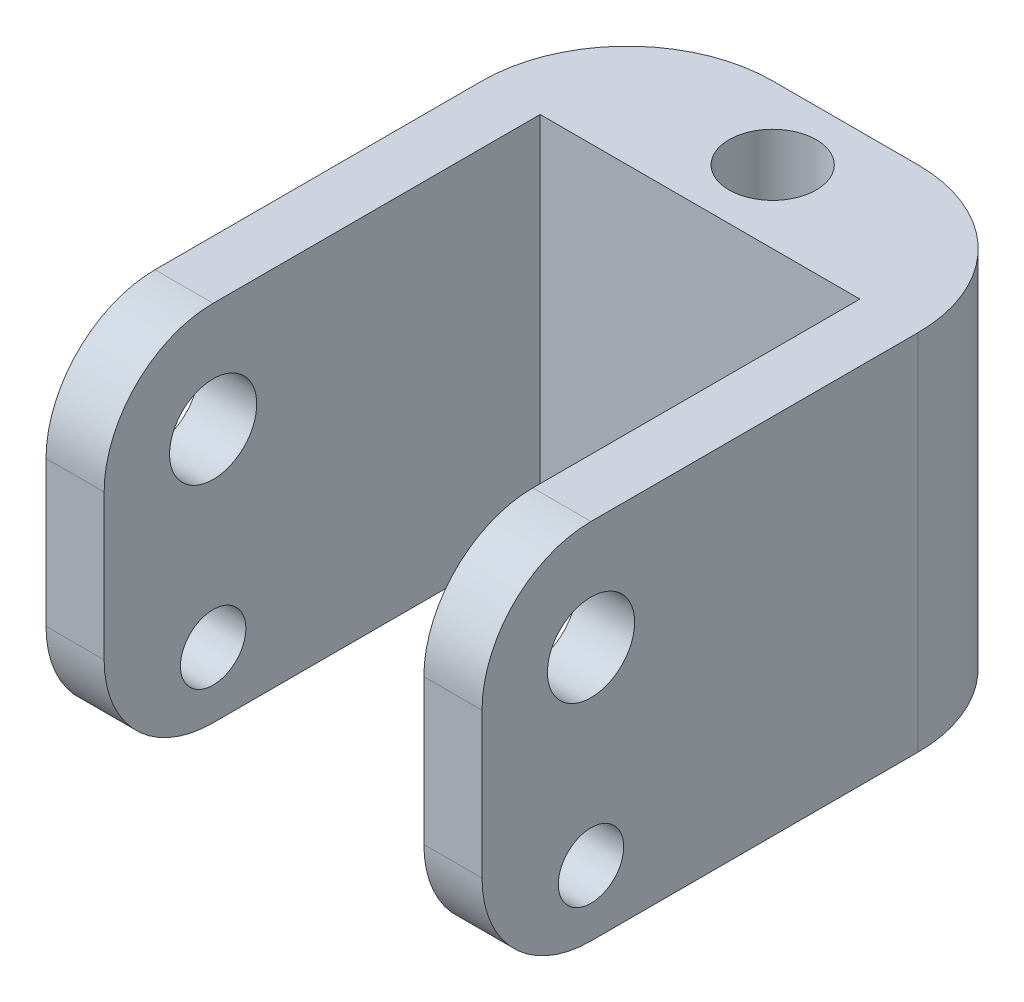
SolidWorks part; units mm, degrees
ref_plane "Front Plane" through (0, 0, 0) normal (0, 0, 1) x (1, 0, 0)
ref_plane "Top Plane" through (0, 0, 0) normal (0, 1, 0) x (1, 0, 0)
ref_plane "Right Plane" through (0, 0, 0) normal (1, 0, 0) x (0, 0, -1)
sketch "Sketch4" plane through (0, 0, 0) normal (1, 0, 0) x (0, 0, -1)
  line L1 (-40, -25) -> (40, -25)
  line L2 (-40, -25) -> (-40, 25)
  line L3 (-40, 25) -> (40, 25)
  line L4 (40, -25) -> (40, 25)
  line L5 (-40, -25) -> (40, 25) construction
  line L6 (-40, 25) -> (40, -25) construction
  line L7 (-25, 10) -> (-25, -16) construction
  circle A0 centre (-25, 10) radius 6
  circle A1 centre (-25, -16) radius 4.5
  circle A2 centre (-25, 10) radius 26 construction
  point P0 (0, 0)
  dimension "D3" = 12
  dimension "D4" = 15
  dimension "D5" = 15
  dimension "D6" = 9
  dimension "D7" = 52
  dimension "D1" = 50
  dimension "D2" = 80
extrude "Boss-Extrude2" add sketch "Sketch4" along normal mid plane 60
sketch "Sketch5" plane through (0, 0, 0) normal (0, 1, 0) x (1, 0, 0)
  line L0 (30, -40) -> (-30, -40) construction
  line L1 (-22, -40) -> (22, -40)
  line L2 (-22, -40) -> (-22, 20)
  line L3 (-22, 20) -> (22, 20)
  line L4 (22, -40) -> (22, 20)
  line L5 (0, 0) -> (0, -40) construction
  line L6 (20, -15.6599) -> (20, -62.9706) construction
  dimension "D1" = 2
  dimension "D2" = 60
extrude "Cut-Extrude3" cut sketch "Sketch5" against normal through all both and the other way through all
sketch "Sketch6" plane through (0, 0, 0) normal (0, 1, 0) x (1, 0, 0)
  line L0 (30, 40) -> (-30, 40) construction
  circle A0 centre (0, 30) radius 6
  dimension "D1" = 12
  dimension "D2" = 10
extrude "Cut-Extrude4" cut sketch "Sketch6" against normal through all both and the other way through all
fillet "Fillet1" radius 20 2 edges at (-30, 0, -40) (30, 0, -40)
fillet "Fillet3" radius 15 4 edges at (-26, 25, 40) (-26, -25, 40) (26, -25, 40) (26, 25, 40)
